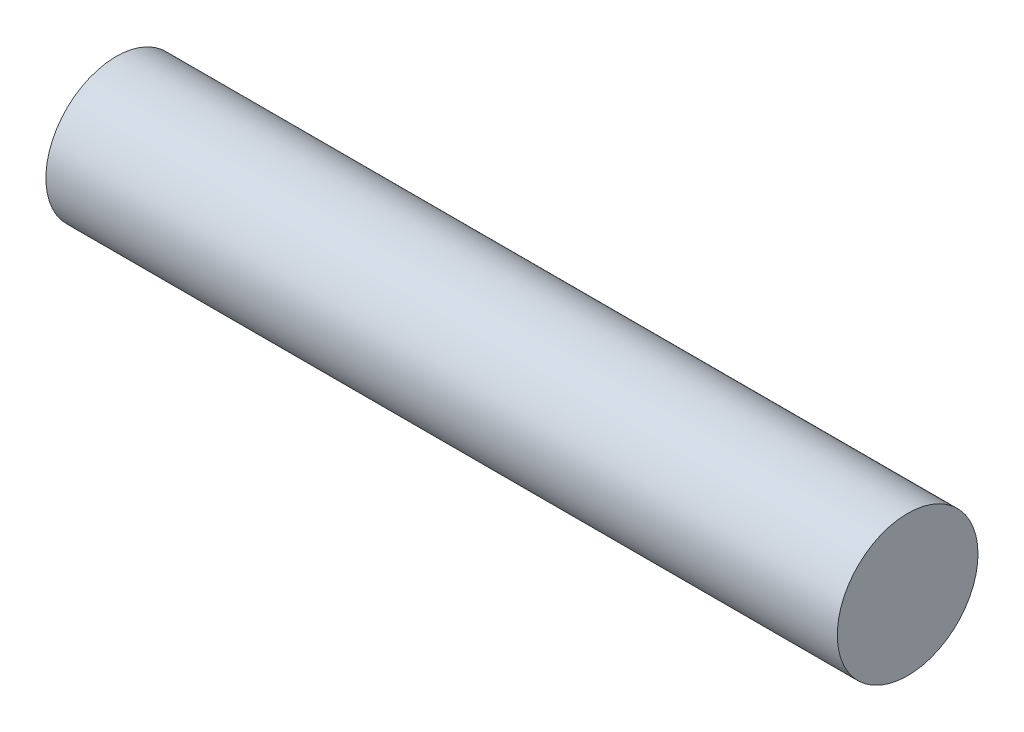
SolidWorks part; units mm, degrees
ref_plane "Front Plane" through (0, 0, 0) normal (0, 0, 1) x (1, 0, 0)
ref_plane "Top Plane" through (0, 0, 0) normal (0, 1, 0) x (1, 0, 0)
ref_plane "Right Plane" through (0, 0, 0) normal (1, 0, 0) x (0, 0, -1)
sketch "Sketch1" plane through (0, 0, 0) normal (1, 0, 0) x (0, 0, -1)
  circle A0 centre (0, 0) radius 0.8
  dimension "D1" = 1.6
extrude "Boss-Extrude1" add sketch "Sketch1" along normal blind 9
